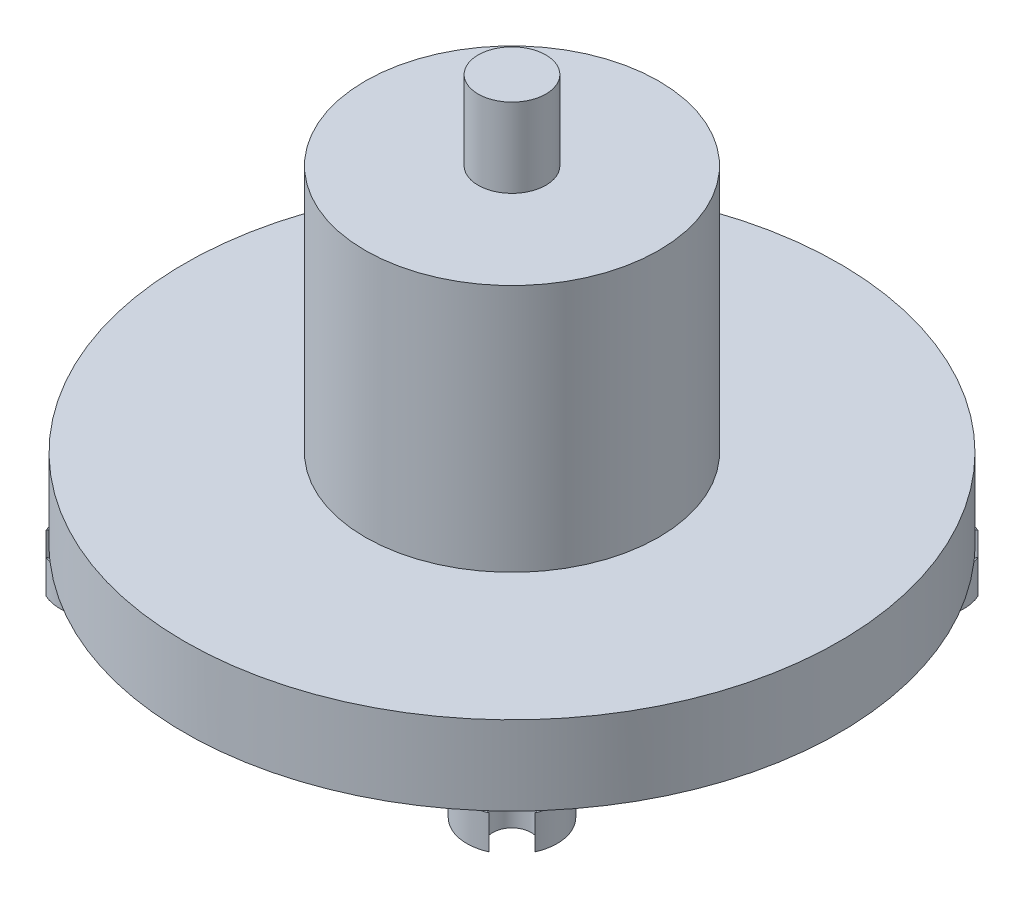
SolidWorks part; units mm, degrees
ref_plane "Front Plane" through (0, 0, 0) normal (0, 0, 1) x (1, 0, 0)
ref_plane "Top Plane" through (0, 0, 0) normal (0, 1, 0) x (1, 0, 0)
ref_plane "Right Plane" through (0, 0, 0) normal (1, 0, 0) x (0, 0, -1)
sketch "Sketch1" plane through (0, 0, 0) normal (0, 1, 0) x (1, 0, 0)
  circle A0 centre (0, 0) radius 58
extrude "Boss-Extrude1" add sketch "Sketch1" along normal blind 14
sketch "Sketch2" plane through (0, 0, 0) normal (0, 1, 0) x (1, 0, 0)
  circle A0 centre (-36, -36) radius 8
  circle A1 centre (36, -36) radius 8
  circle A2 centre (-36, 36) radius 8
  circle A3 centre (36, 36) radius 8
extrude "Boss-Extrude2" add sketch "Sketch2" against normal blind 6
sketch "Sketch3" plane through (0, 0, 0) normal (0, 1, 0) x (1, 0, 0)
  circle A0 centre (0, 0) radius 26
extrude "Boss-Extrude3" add sketch "Sketch3" along normal blind 58
sketch "Sketch4" plane through (0, 0, 0) normal (0, 1, 0) x (1, 0, 0)
  circle A0 centre (0, 0) radius 6
extrude "Boss-Extrude4" add sketch "Sketch4" along normal blind 72
sketch "Sketch5" plane through (0, 0, 0) normal (0, 1, 0) x (1, 0, 0)
  circle A0 centre (-40, -40) radius 3.4
  circle A1 centre (40, -40) radius 3.4
  circle A2 centre (-40, 40) radius 3.4
  circle A3 centre (40, 40) radius 3.4
extrude "Cut-Extrude1" cut sketch "Sketch5" against normal through all
